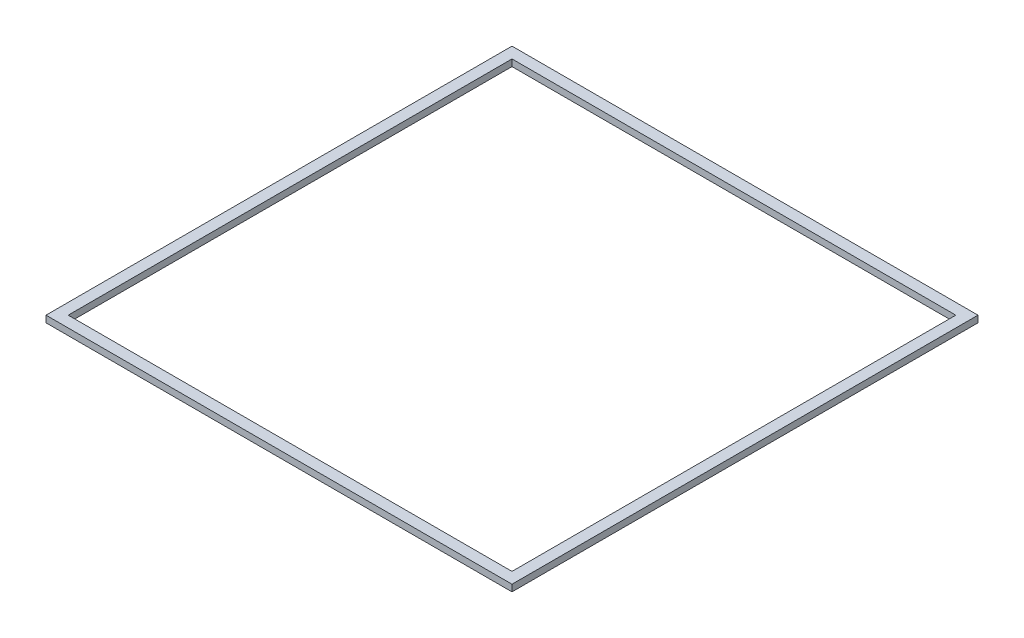
SolidWorks part; units mm, degrees
ref_plane "Alzado" through (0, 0, 0) normal (0, 0, 1) x (1, 0, 0)
ref_plane "Planta" through (0, 0, 0) normal (0, 1, 0) x (1, 0, 0)
ref_plane "Vista lateral" through (0, 0, 0) normal (1, 0, 0) x (0, 0, -1)
sketch "Sketch1" plane through (0, 0, 0) normal (0, 1, 0) x (1, 0, 0)
  line L5 (0, 27.29) -> (210, 27.29)
  line L6 (0, 27.29) -> (0, 237.29)
  line L11 (0, 237.29) -> (210, 237.29)
  line L12 (210, 27.29) -> (210, 237.29)
  line L13 (0, 27.29) -> (210, 237.29) construction
  line L14 (0, 237.29) -> (210, 27.29) construction
  line L15 (5, 232.29) -> (205, 232.29)
  line L16 (5, 232.29) -> (5, 32.29)
  line L17 (5, 32.29) -> (205, 32.29)
  line L18 (205, 232.29) -> (205, 32.29)
  line L19 (5, 232.29) -> (205, 32.29) construction
  line L20 (5, 32.29) -> (205, 232.29) construction
  point P4 (135.3657, 118.645)
  point P10 (104.7164, 132.5736)
  dimension "D1" = 210
  dimension "D2" = 210
  dimension "D3" = 200
  dimension "D4" = 200
  dimension "D5" = 5
  dimension "D6" = 5
extrude "Boss-Extrude1" add sketch "Sketch1" along normal blind 3
